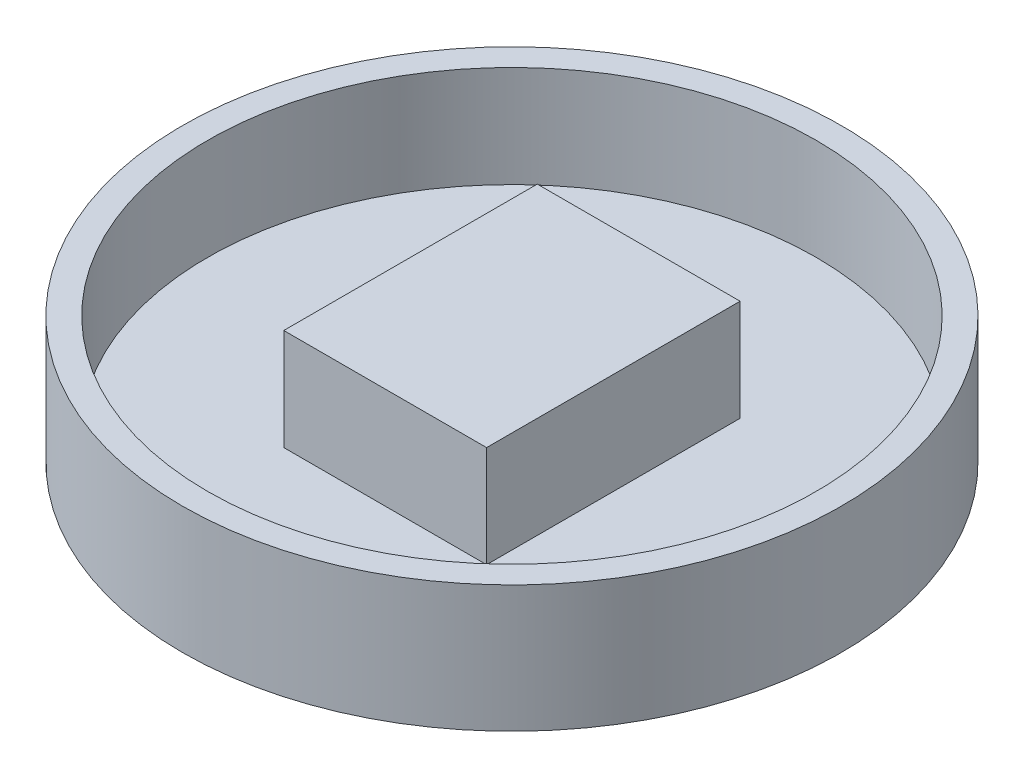
SolidWorks part; units mm, degrees
ref_plane "Front Plane" through (0, 0, 0) normal (0, 0, 1) x (1, 0, 0)
ref_plane "Top Plane" through (0, 0, 0) normal (0, 1, 0) x (1, 0, 0)
ref_plane "Right Plane" through (0, 0, 0) normal (1, 0, 0) x (0, 0, -1)
sketch "Sketch1" plane through (0, 0, 0) normal (0, 1, 0) x (1, 0, 0)
  circle A0 centre (0, 0) radius 65
extrude "Boss-Extrude2" add sketch "Sketch1" along normal blind 25
sketch "Sketch2" plane through (0, 25, 0) normal (0, 1, 0) x (1, 0, 0)
  circle A0 centre (0, 0) radius 60
extrude "Cut-Extrude1" cut sketch "Sketch2" against normal blind 20
sketch "Sketch3" plane through (0, 5, 0) normal (0, 1, 0) x (1, 0, 0)
  line L1 (-20, 25) -> (20, 25)
  line L2 (-20, 25) -> (-20, -25)
  line L3 (-20, -25) -> (20, -25)
  line L4 (20, 25) -> (20, -25)
  line L5 (-20, 25) -> (20, -25) construction
  line L6 (-20, -25) -> (20, 25) construction
  point P0 (0, 0)
  point P6 (0, 0)
  point P7 (0, 25)
  point P8 (0, 0)
  point P9 (0, 0)
  dimension "D1" = 50
  dimension "D2" = 40
  dimension "D3" = 25
  dimension "D4" = 25
extrude "Boss-Extrude3" add sketch "Sketch3" along normal blind 20
sketch "Sketch4" plane through (0, 0, 0) normal (0, -1, 0) x (1, 0, 0)
  line L1 (-17.5, 23) -> (17.5, 23)
  line L2 (-17.5, 23) -> (-17.5, -5)
  line L3 (-17.5, -5) -> (17.5, -5)
  line L4 (17.5, 23) -> (17.5, -5)
  line L5 (-17.5, 23) -> (17.5, -5) construction
  line L6 (-17.5, -5) -> (17.5, 23) construction
  circle A0 centre (0, 0) radius 65 construction
  point P0 (0, 9)
  point P5 (0, 0)
  point P6 (0, -5)
  dimension "D1" = 5
  dimension "D2" = 35
extrude "Cut-Extrude2" cut sketch "Sketch4" against normal blind 18
